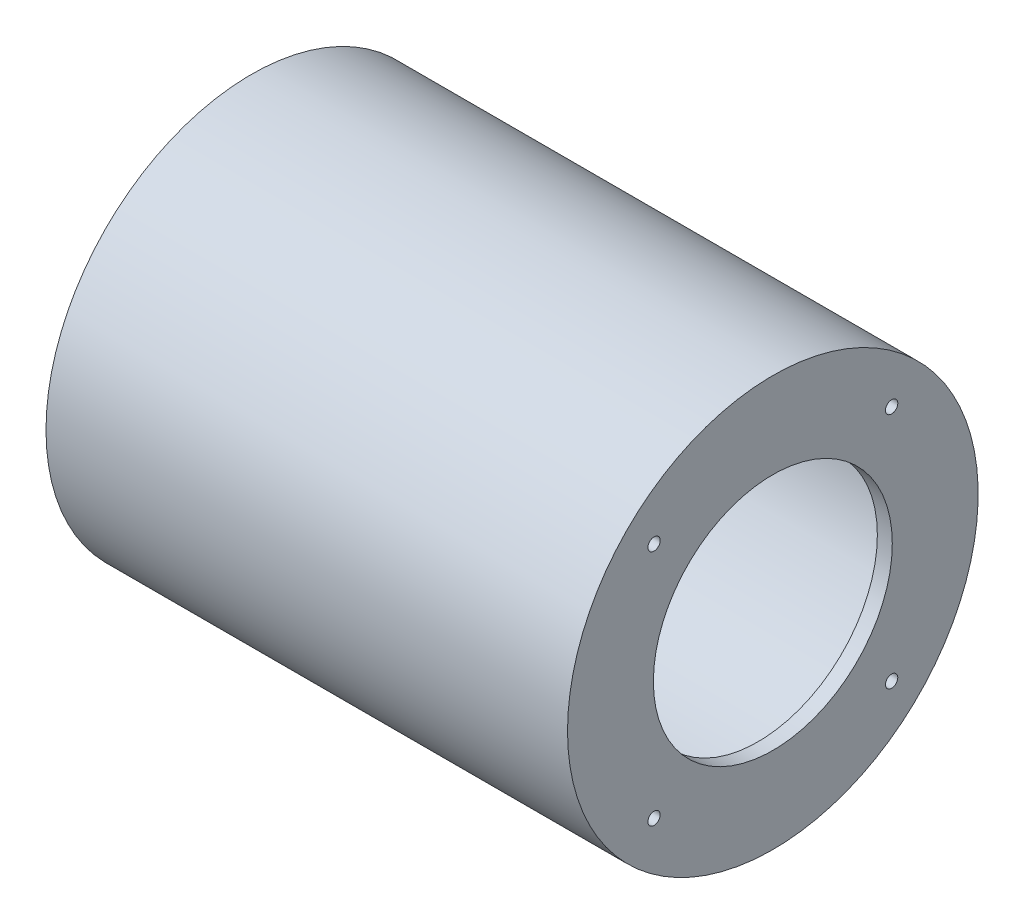
SolidWorks part; units mm, degrees
material "AISI 304"
ref_plane "Front Plane" through (0, 0, 0) normal (0, 0, 1) x (1, 0, 0)
ref_plane "Top Plane" through (0, 0, 0) normal (0, 1, 0) x (1, 0, 0)
ref_plane "Right Plane" through (0, 0, 0) normal (1, 0, 0) x (0, 0, -1)
sketch "Axial profile (mm)" plane through (0, 0, 0) normal (0, 0, 1) x (1, 0, 0)
  line L0 (-110, 0) -> (75, 0) construction
  line L1 (-126, 49) -> (9.7, 49)
  line L2 (9.7, 49) -> (9.7, 32)
  line L3 (9.7, 32) -> (13.7, 32)
  line L4 (13.7, 32) -> (13.7, 55)
  line L5 (13.7, 55) -> (-126, 55)
  line L6 (-126, 55) -> (-126, 49)
revolve "Full revolution" add sketch "Axial profile (mm)" angle 360 about L0
sketch "Sketch2" plane through (0, 0, 0) normal (1, 0, 0) x (0, 0, -1)
  circle A0 centre (-31.8198, 31.8198) radius 1.65
  circle A1 centre (-31.8198, -31.8198) radius 1.65
  circle A2 centre (31.8198, -31.8198) radius 1.65
  circle A3 centre (31.8198, 31.8198) radius 1.65
extrude "Axial holes" cut sketch "Sketch2" along normal blind 4 from offset 9.7
sketch "Sketch3" plane through (0, 0, 0) normal (1, 0, 0) x (0, 0, -1)
  circle A0 centre (0, 52) radius 1.55
  circle A1 centre (-52, 0) radius 1.55
  circle A2 centre (0, -52) radius 1.55
  circle A3 centre (52, 0) radius 1.55
extrude "Cut-Extrude2" cut sketch "Sketch3" along normal blind 6 from offset 126
